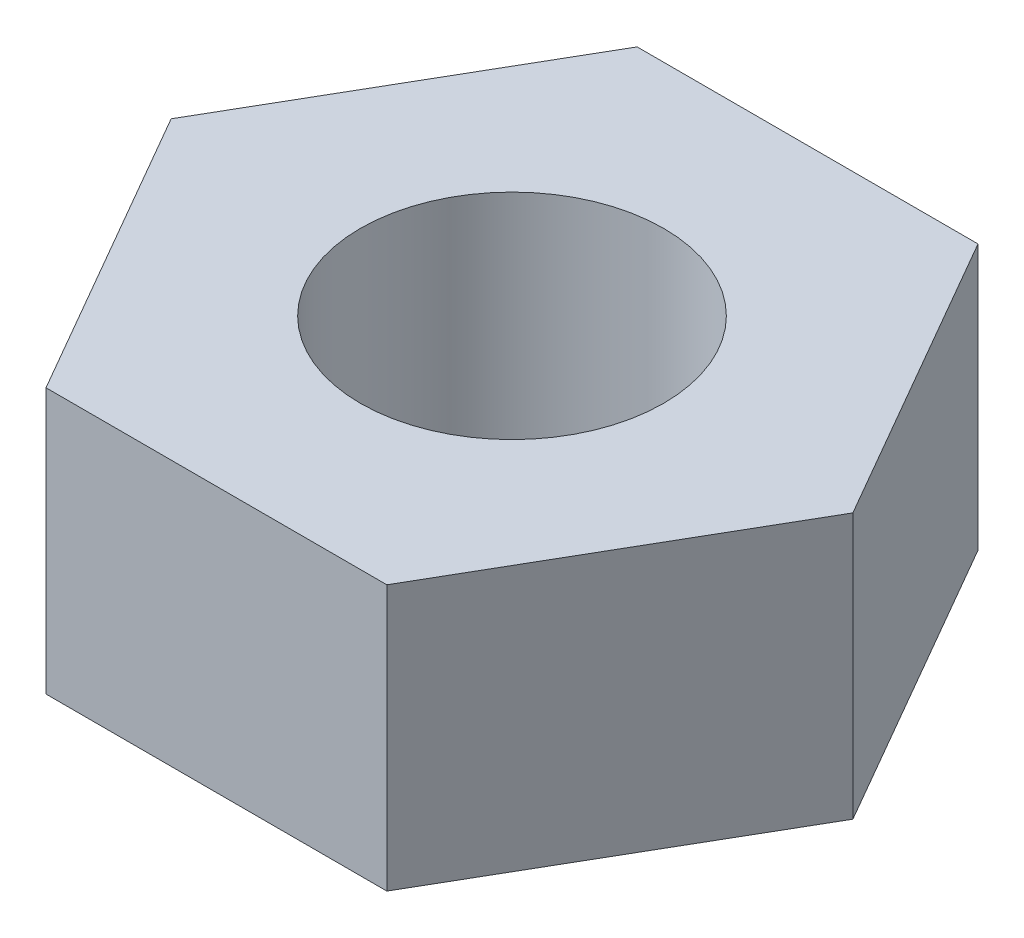
SolidWorks part; units mm, degrees
ref_plane "Спереди" through (0, 0, 0) normal (0, 0, 1) x (1, 0, 0)
ref_plane "Сверху" through (0, 0, 0) normal (0, 1, 0) x (1, 0, 0)
ref_plane "Справа" through (0, 0, 0) normal (1, 0, 0) x (0, 0, -1)
sketch "Эскиз1" plane through (0, 0, 0) normal (0, 1, 0) x (1, 0, 0)
  line L1 (8.9903, -15.5941) -> (18, -0.0113)
  line L2 (18, -0.0113) -> (9.0097, 15.5828)
  line L3 (9.0097, 15.5828) -> (-8.9903, 15.5941)
  line L4 (-8.9903, 15.5941) -> (-18, 0.0113)
  line L5 (-18, 0.0113) -> (-9.0097, -15.5828)
  line L6 (-9.0097, -15.5828) -> (8.9903, -15.5941)
  circle A0 centre (0, 0) radius 8
  circle A1 centre (0, 0) radius 15.5885 construction
extrude "Вытянуть1" add sketch "Эскиз1" along normal blind 14
